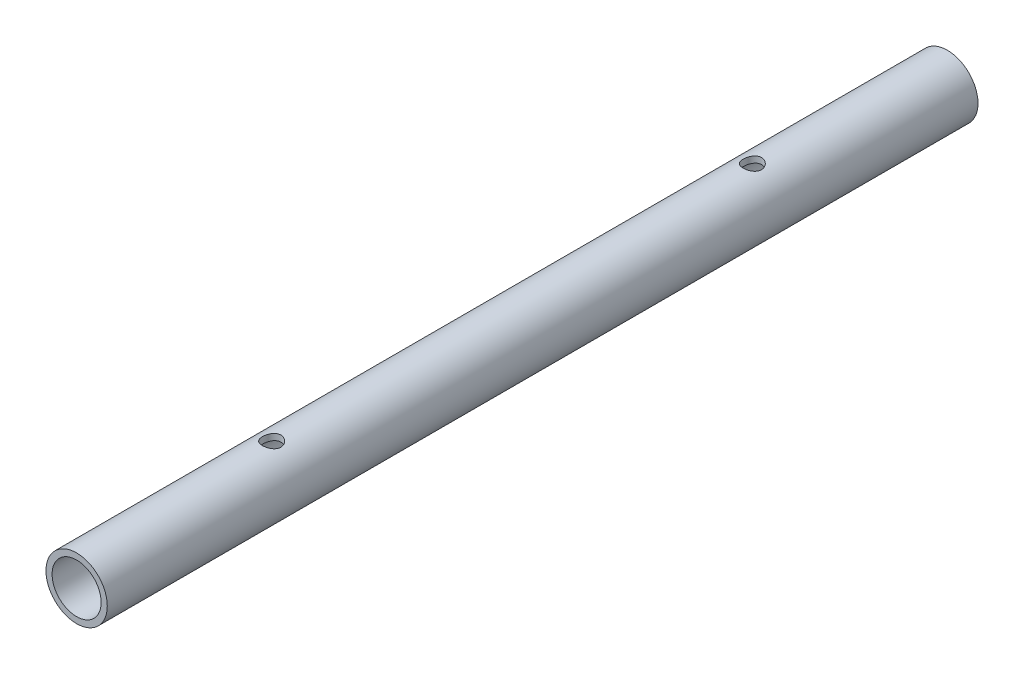
SolidWorks part; units mm, degrees
ref_plane "Plan de face" through (0, 0, 0) normal (0, 0, 1) x (1, 0, 0)
ref_plane "Plan de dessus" through (0, 0, 0) normal (0, 1, 0) x (1, 0, 0)
ref_plane "Plan de droite" through (0, 0, 0) normal (1, 0, 0) x (0, 0, -1)
sketch "Sketch1" plane through (0, 0, 0) normal (0, 0, 1) x (1, 0, 0)
  circle A0 centre (0, 0) radius 5
extrude "Boss-Extrude1" add sketch "Sketch1" along normal blind 141.96
sketch "Sketch2" plane through (0, 0, 141.96) normal (0, 0, 1) x (1, 0, 0)
  circle A0 centre (0, 0) radius 4
extrude "Cut-Extrude1" cut sketch "Sketch2" against normal up to next
sketch "Sketch5" plane through (0, 0, 0) normal (0, 1, 0) x (1, 0, 0)
  circle A0 centre (0, -31.799) radius 1.5
  circle A1 centre (0, -110.161) radius 1.5
  dimension "D1" = 31.799
  dimension "D2" = 110.161
extrude "Cut-Extrude2" cut sketch "Sketch5" against normal through all and the other way through all
